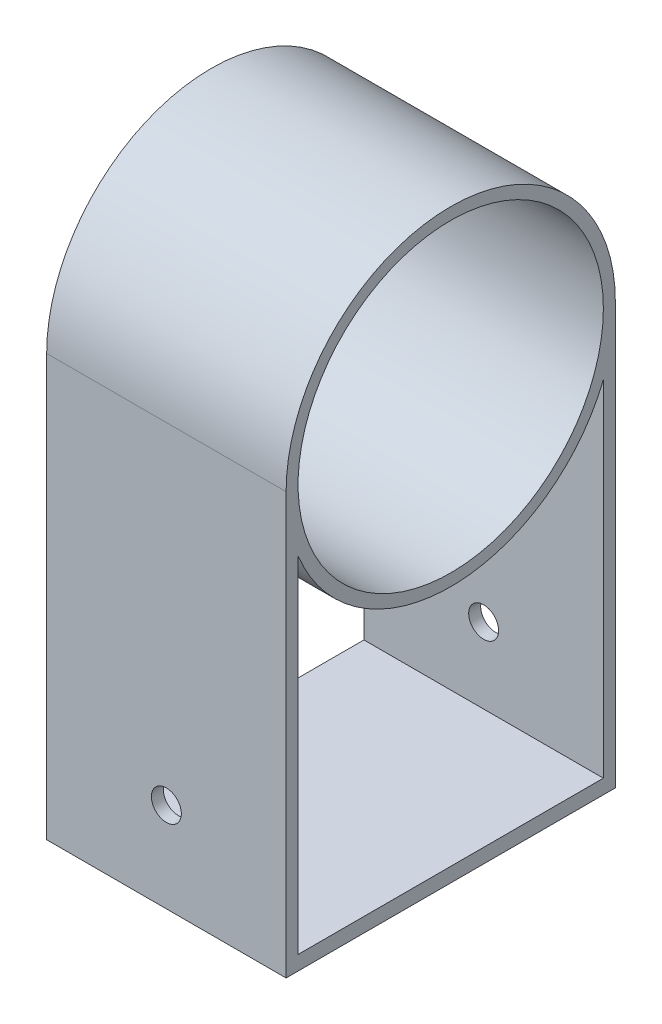
SolidWorks part; units mm, degrees
ref_plane "Front Plane" through (0, 0, 0) normal (0, 0, 1) x (1, 0, 0)
ref_plane "Top Plane" through (0, 0, 0) normal (0, 1, 0) x (1, 0, 0)
ref_plane "Right Plane" through (0, 0, 0) normal (1, 0, 0) x (0, 0, -1)
sketch "Sketch1" plane through (0, 0, 0) normal (1, 0, 0) x (0, 0, -1)
  line L0 (-25.5, -10.2956) -> (-25.5, -67.9456)
  line L1 (-25.5, -67.9456) -> (25.5, -67.9456)
  line L2 (25.5, -67.9456) -> (25.5, -10.2956)
  line L3 (-27.5, 0) -> (-27.5, -70.3541)
  line L4 (-27.5, -70.3541) -> (27.5, -70.3541)
  line L5 (27.5, -70.3541) -> (27.5, 0)
  circle A0 centre (0, 0) radius 25.5
  arc A1 (27.5, 0) -> (-27.5, 0) centre (0, 0) ccw
  arc A2 (-25.5, -10.2956) -> (25.5, -10.2956) centre (0, 0) ccw
  dimension "D1" = 51
  dimension "D2" = 55
extrude "Boss-Extrude1" add sketch "Sketch1" against normal blind 40
sketch "Sketch2" plane through (0, 0, 27.5) normal (0, 0, 1) x (1, 0, 0)
  line L0 (-40, -70.3541) -> (0, -70.3541) construction
  circle A0 centre (-20, -55.3541) radius 2.5
  dimension "D1" = 5
  dimension "D2" = 15
extrude "Cut-Extrude1" cut sketch "Sketch2" against normal through all
